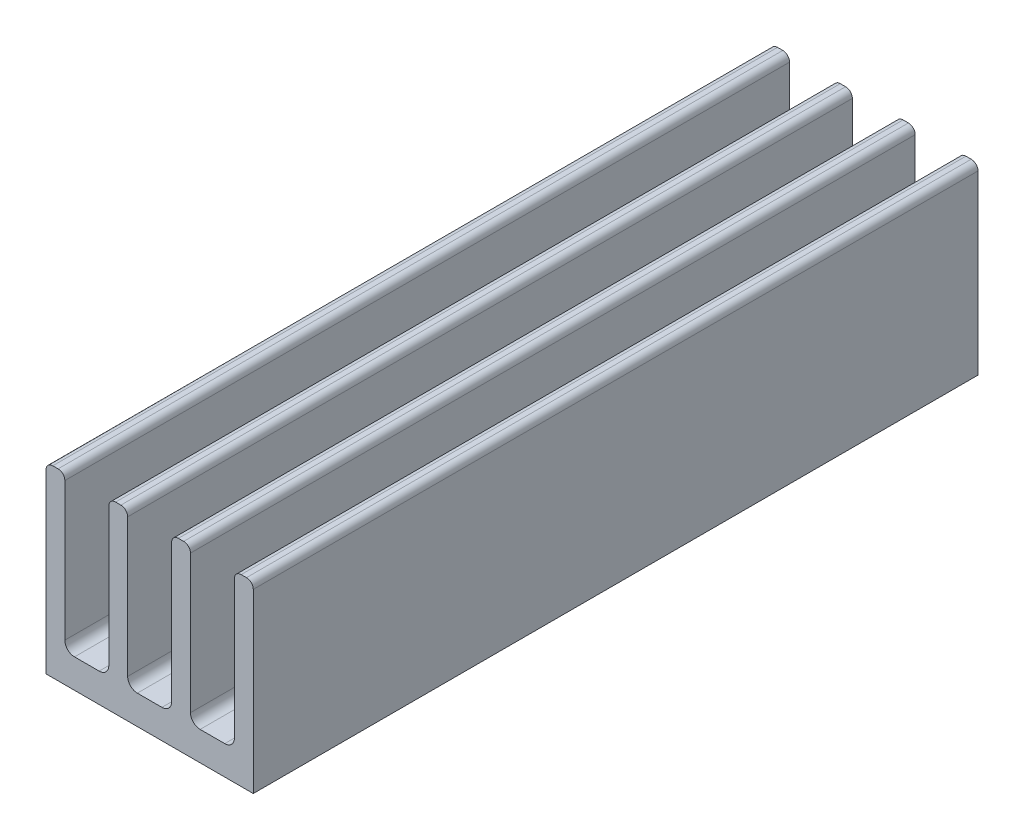
SolidWorks part; units mm, degrees
ref_plane "Front Plane" through (0, 0, 0) normal (0, 0, 1) x (1, 0, 0)
ref_plane "Top Plane" through (0, 0, 0) normal (0, 1, 0) x (1, 0, 0)
ref_plane "Right Plane" through (0, 0, 0) normal (1, 0, 0) x (0, 0, -1)
sketch "Model" plane through (0, 0, 0) normal (0, 0, 1) x (1, 0, 0)
  line L0 (12.0487, 3) -> (10.7737, 3)
  line L1 (10.7737, 3) -> (9.4987, 3)
  line L2 (8.4987, 4) -> (8.4987, 18.3)
  line L3 (7.7987, 19) -> (7.2487, 19)
  line L4 (6.5487, 18.3) -> (6.5487, 4)
  line L5 (5.5487, 3) -> (2.9987, 3)
  line L6 (1.9987, 4) -> (1.9987, 18.3)
  line L7 (1.2987, 19) -> (0.7487, 19)
  line L8 (0.0487, 18.3) -> (0.0487, 0)
  line L9 (0.0487, 0) -> (10.7737, 0)
  line L10 (10.7737, 0) -> (21.4987, 0)
  line L11 (21.4987, 0) -> (21.4987, 18.3)
  line L12 (20.7987, 19) -> (20.2487, 19)
  line L13 (19.5487, 18.3) -> (19.5487, 4)
  line L14 (18.5487, 3) -> (15.9987, 3)
  line L15 (14.9987, 4) -> (14.9987, 18.3)
  line L16 (14.2987, 19) -> (13.7487, 19)
  line L17 (13.0487, 18.3) -> (13.0487, 4)
  arc A0 (8.4987, 4) -> (9.4987, 3) centre (9.4987, 4) ccw
  arc A1 (8.4987, 18.3) -> (7.7987, 19) centre (7.7987, 18.3) ccw
  arc A2 (7.2487, 19) -> (6.5487, 18.3) centre (7.2487, 18.3) ccw
  arc A3 (5.5487, 3) -> (6.5487, 4) centre (5.5487, 4) ccw
  arc A4 (1.9987, 4) -> (2.9987, 3) centre (2.9987, 4) ccw
  arc A5 (1.9987, 18.3) -> (1.2987, 19) centre (1.2987, 18.3) ccw
  arc A6 (0.7487, 19) -> (0.0487, 18.3) centre (0.7487, 18.3) ccw
  arc A7 (21.4987, 18.3) -> (20.7987, 19) centre (20.7987, 18.3) ccw
  arc A8 (20.2487, 19) -> (19.5487, 18.3) centre (20.2487, 18.3) ccw
  arc A9 (18.5487, 3) -> (19.5487, 4) centre (18.5487, 4) ccw
  arc A10 (14.9987, 4) -> (15.9987, 3) centre (15.9987, 4) ccw
  arc A11 (14.9987, 18.3) -> (14.2987, 19) centre (14.2987, 18.3) ccw
  arc A12 (13.7487, 19) -> (13.0487, 18.3) centre (13.7487, 18.3) ccw
  arc A13 (12.0487, 3) -> (13.0487, 4) centre (12.0487, 4) ccw
extrude "Boss-Extrude1" add sketch "Model" along normal blind 75
